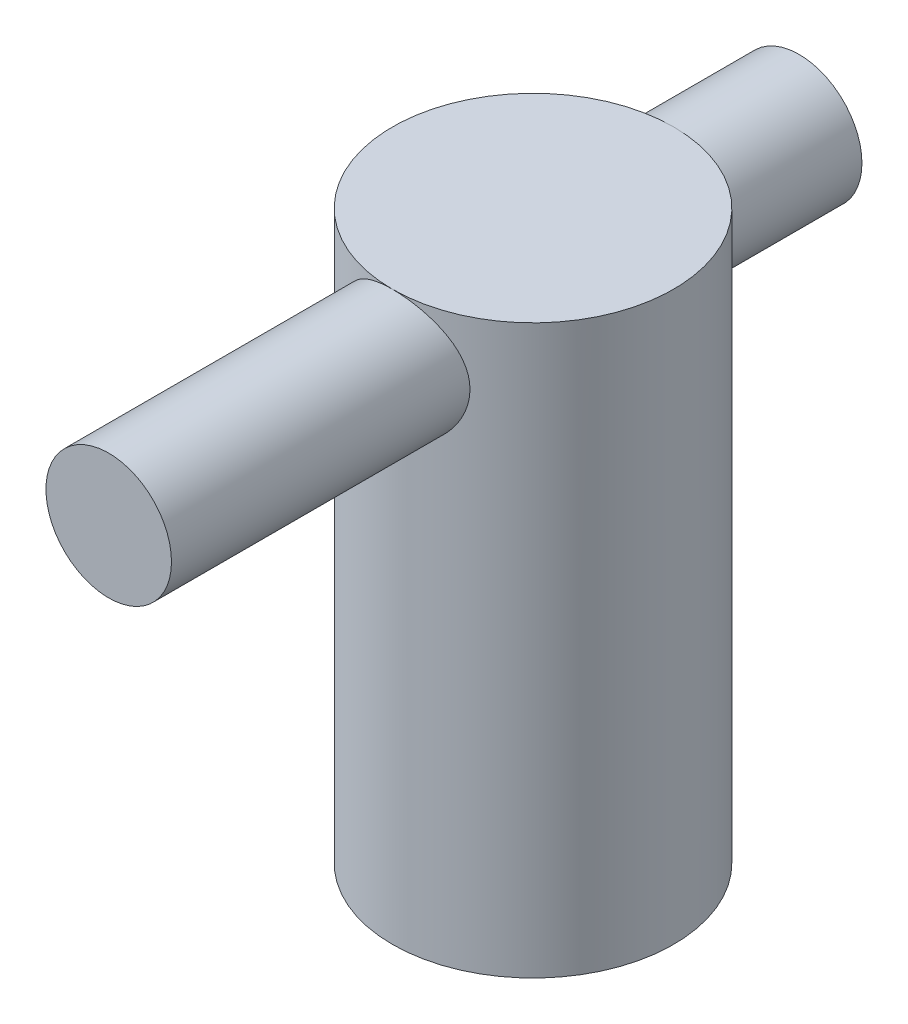
SolidWorks part; units mm, degrees
ref_plane "Front Plane" through (0, 0, 0) normal (0, 0, 1) x (1, 0, 0)
ref_plane "Top Plane" through (0, 0, 0) normal (0, 1, 0) x (1, 0, 0)
ref_plane "Right Plane" through (0, 0, 0) normal (1, 0, 0) x (0, 0, -1)
sketch "Sketch2" plane through (0, 0, 0) normal (0, 1, 0) x (1, 0, 0)
  circle A0 centre (0, 0) radius 14.224
  dimension "D1" = 28.448
extrude "Boss-Extrude1" add sketch "Sketch2" along normal blind 57.404
ref_plane "Plane1" through (0, 0, 14.224) normal (0, 0, 1) x (1, 0, 0)
sketch "Sketch3" plane through (0, 0, 14.224) normal (0, 0, 1) x (1, 0, 0)
  line L0 (0, 62.6796) -> (0, -4.0923) construction
  line L1 (14.224, 57.404) -> (-14.224, 57.404) construction
  circle A0 centre (0, 51.054) radius 6.35
  dimension "D1" = 12.7
  dimension "D2" = 6.35
extrude "Boss-Extrude2" add sketch "Sketch3" along normal blind 28.702 and the other way blind 41.148
